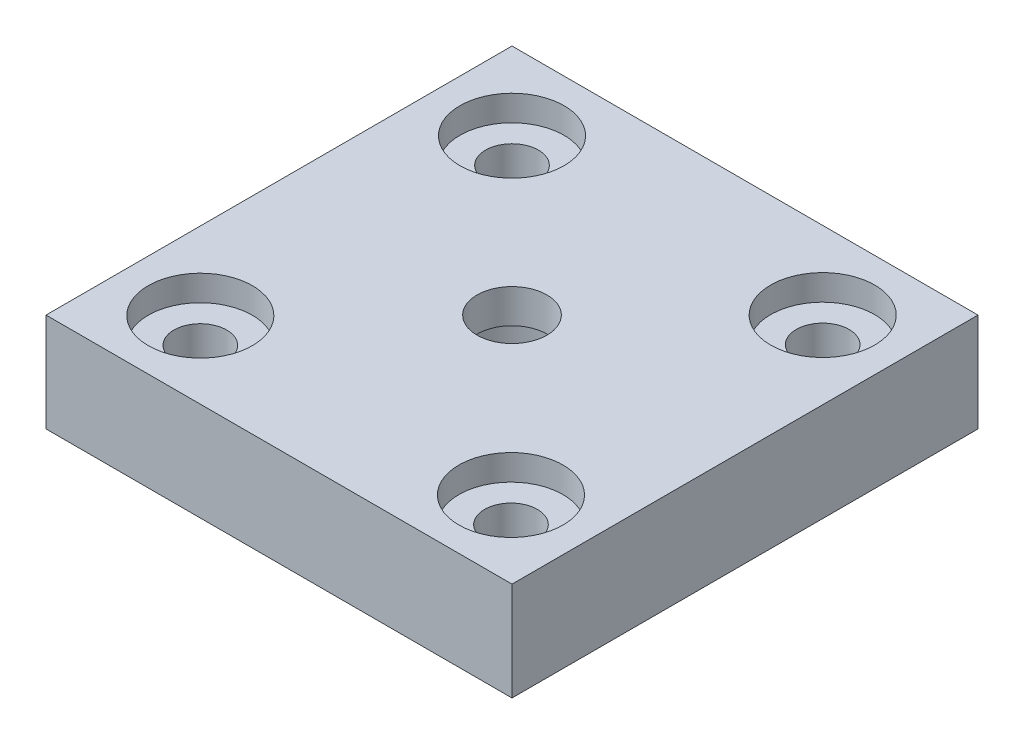
SolidWorks part; units mm, degrees
ref_plane "Front Plane" through (0, 0, 0) normal (0, 0, 1) x (1, 0, 0)
ref_plane "Top Plane" through (0, 0, 0) normal (0, 1, 0) x (1, 0, 0)
ref_plane "Right Plane" through (0, 0, 0) normal (1, 0, 0) x (0, 0, -1)
sketch "Sketch1" plane through (0, 0, 0) normal (0, 1, 0) x (1, 0, 0)
  line L1 (-15, -15) -> (15, -15)
  line L2 (-15, -15) -> (-15, 15)
  line L3 (-15, 15) -> (15, 15)
  line L4 (15, -15) -> (15, 15)
  point P7 (15, 0)
  point P8 (0, 15)
  dimension "D1" = 30
  dimension "D2" = 30
extrude "Mount Block" add sketch "Sketch1" along normal blind 6.35
hole_wizard "Linear Stage CBORE for M3 SBHCS1" positions "Sketch2" profile "Sketch3" counterbore size "M3" standard "ANSI Metric" end condition through all
sketch "Sketch2" plane through (0, 6.35, 0) normal (0, 1, 0) x (1, 0, 0)
  point P0 (-10, 10)
  point P7 (10, 10)
  point P8 (10, -10.066)
  point P9 (-10, -10.066)
  dimension "D3" = 10
  dimension "D4" = 10
  dimension "D1" = 2
  dimension "D2" = 2
sketch "Sketch3" plane through (-10, 6.35, -10) normal (1, 0, 0) x (0, 0, 1)
  line L0 (0, 0) -> (0, 6.35)
  line L1 (0, 6.35) -> (1.7, 6.35)
  line L3 (1.7, 6.35) -> (1.7, 1.65)
  line L4 (1.7, 1.65) -> (3.35, 1.65)
  line L5 (3.35, 1.65) -> (3.35, 0)
  line L7 (3.35, 0) -> (0, 0)
  line L11 (0, -6.35) -> (0, 107.95) construction
  dimension "Thru Hole Dia." = 3.4
  dimension "Thru Hole Depth" = 6.35
  dimension "C'Bore Dia." = 6.7
  dimension "C'Bore Depth" = 1.65
hole_wizard "Optical Post CBORE for #8 Socket Head Cap Screw" positions "Sketch6" profile "Sketch7" counterbore size "#8" standard "ANSI Inch" end condition through all
sketch "Sketch6" plane through (0, 0, 0) normal (0, -1, 0) x (-1, 0, 0)
  point P0 (0, 0)
sketch "Sketch7" plane through (0, 0, 0) normal (1, 0, 0) x (0, 0, -1)
  line L0 (0, 0) -> (0, 6.35)
  line L1 (0, 6.35) -> (2.2479, 6.35)
  line L3 (2.2479, 6.35) -> (2.2479, 4.1656)
  line L4 (2.2479, 4.1656) -> (3.9688, 4.1656)
  line L5 (3.9688, 4.1656) -> (3.9688, 0)
  line L7 (3.9688, 0) -> (0, 0)
  line L11 (0, -6.35) -> (0, 107.95) construction
  dimension "Thru Hole Dia." = 4.4958
  dimension "Thru Hole Depth" = 6.35
  dimension "C'Bore Dia." = 7.9375
  dimension "C'Bore Depth" = 4.1656
